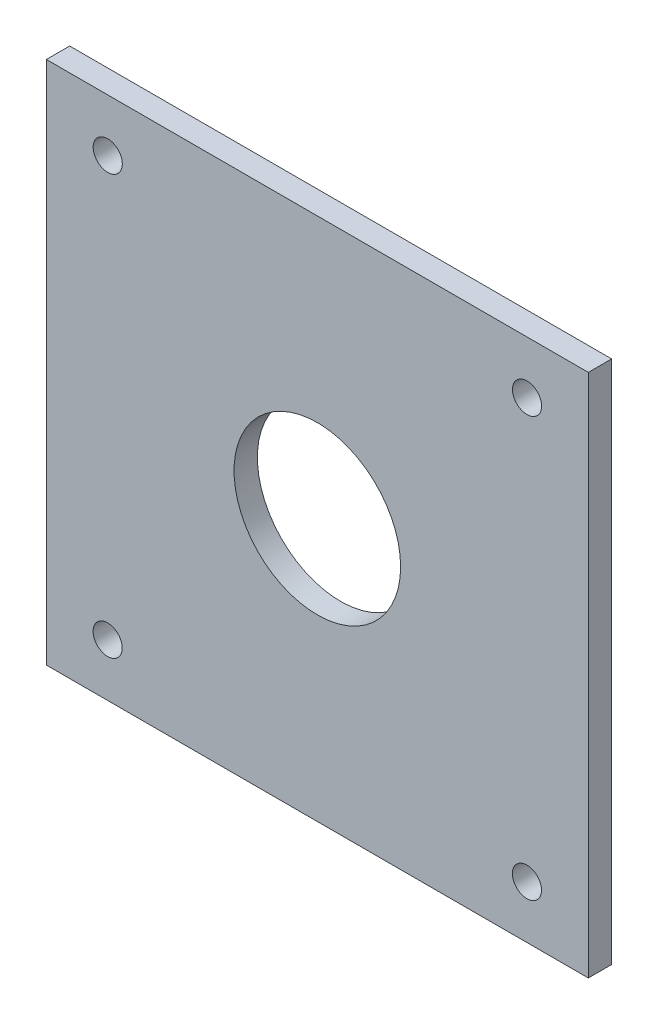
SolidWorks part; units mm, degrees
ref_plane "Front Plane" through (0, 0, 0) normal (0, 0, 1) x (1, 0, 0)
ref_plane "Top Plane" through (0, 0, 0) normal (0, 1, 0) x (1, 0, 0)
ref_plane "Right Plane" through (0, 0, 0) normal (1, 0, 0) x (0, 0, -1)
sketch "Sketch1" plane through (0, 0, 0) normal (0, 0, 1) x (1, 0, 0)
  line L0 (0, 14.29) -> (0, -14.29) construction
  line L5 (-9.359, -10.7988) -> (9.359, 10.7988) construction
  line L6 (-9.359, 10.7988) -> (9.359, -10.7988) construction
  line L7 (46.5, -45) -> (-46.5, -45)
  line L9 (46.5, -45) -> (46.5, 45)
  line L10 (46.5, 45) -> (-46.5, 45)
  line L11 (-46.5, -45) -> (-46.5, 45)
  line L12 (46.5, -45) -> (-46.5, 45) construction
  line L13 (46.5, 45) -> (-46.5, -45) construction
  circle A0 centre (0, 0) radius 14.29
  circle A6 centre (-0.1108, 0.1401) radius 50.375 construction
  circle A14 centre (-35.9815, -35.9666) radius 2.5
  circle A15 centre (-35.9666, 35.9815) radius 2.5
  circle A16 centre (35.9815, 35.9666) radius 2.5
  circle A17 centre (35.9666, -35.9815) radius 2.5
  point P0 (0, 0)
  point P4 (0, 0)
  point P19 (-42.5229, -27.0417)
  point P21 (-0.1108, 0.1401)
  point P22 (0, 0)
  point P27 (-0.1108, 0.1401)
  point P30 (-0.1108, 0.1401)
  point P33 (-0.1108, 0.1401)
  point P34 (-0.1108, 0.1401)
  point P44 (0, 0)
  dimension "D3" = 28.58
  dimension "D1" = 90
  dimension "D2" = 93
  dimension "D4" = 4
  dimension "D5" = 4
extrude "Boss-Extrude1" add sketch "Sketch1" along normal blind 4
